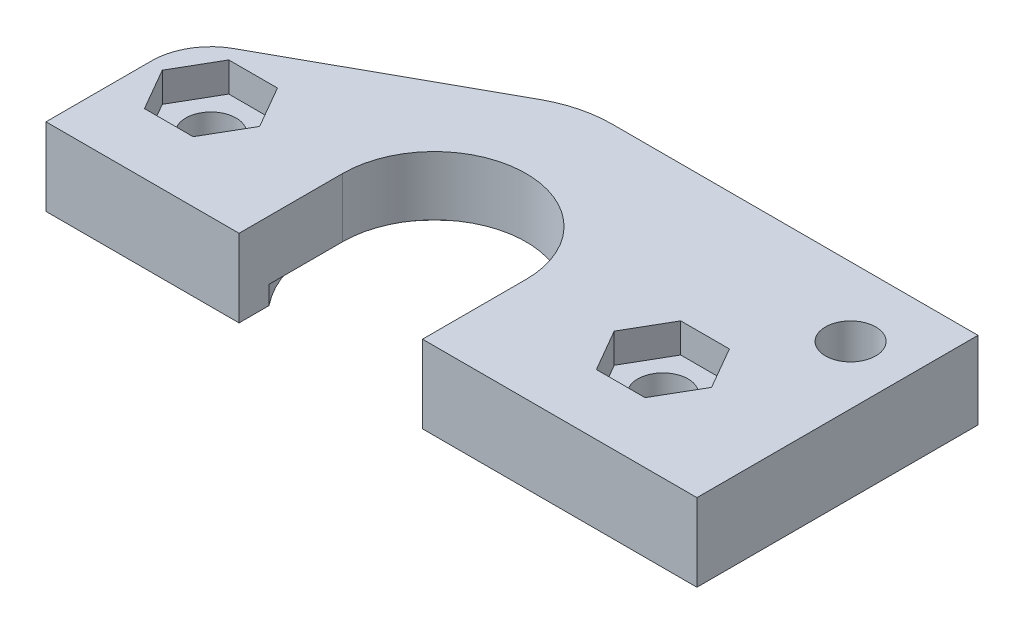
SolidWorks part; units mm, degrees
material "ABS"
ref_plane "Plano frontal" through (0, 0, 0) normal (0, 0, 1) x (1, 0, 0)
ref_plane "Plano superior" through (0, 0, 0) normal (0, 1, 0) x (1, 0, 0)
ref_plane "Plano direito" through (0, 0, 0) normal (1, 0, 0) x (0, 0, -1)
sketch "Esboço1" plane through (0, 0, 0) normal (0, 1, 0) x (1, 0, 0)
  line L0 (13.05, 0) -> (13.05, 7)
  line L1 (0, 0) -> (13.05, 0)
  line L2 (0, 0) -> (0, 9.5)
  line L3 (17.2, 19) -> (44, 19)
  line L4 (44, 0) -> (44, 19)
  line L5 (25.45, 0) -> (25.45, 7)
  line L6 (25.45, 0) -> (44, 0)
  line L7 (0, 9.5) -> (17.2, 19)
  circle A0 centre (4.2, 6.95) radius 1.7
  circle A1 centre (34.75, 6.95) radius 1.7
  circle A2 centre (40.05, 14.3377) radius 1.7
  arc A3 (25.45, 7) -> (13.05, 7) centre (19.25, 7) ccw
  dimension "D3" = 3.4
  dimension "D8" = 3.4
  dimension "D11" = 3.4
  dimension "D13" = 12.4
  dimension "D1" = 44
  dimension "D2" = 19
  dimension "D4" = 4.2
  dimension "D5" = 6.95
  dimension "D6" = 13.05
  dimension "D7" = 12.4
  dimension "D9" = 6.95
  dimension "D10" = 9.25
  dimension "D12" = 3.95
  dimension "D14" = 6.2
  dimension "D15" = 9.5
  dimension "D16" = 26.8
  dimension "D17" = 7
extrude "Ressalto-extrusão1" add sketch "Esboço1" along normal blind 5.25
sketch "Esboço2" plane through (0, 0, 0) normal (0, 1, 0) x (1, 0, 0)
  circle A0 centre (19.25, 7) radius 7.95
extrude "Corte-extrusão1" cut sketch "Esboço2" along normal blind 1.25
fillet "Filete1" radius 4 1 edges at (0, 2.625, -9.5)
fillet "Filete2" radius 8 1 edges at (17.2, 2.625, -19)
sketch "Esboço3" plane through (0, 5.25, 0) normal (0, -1, 0) x (-1, 0, 0)
  line L1 (-31.4591, 6.95) -> (-33.1046, 9.8)
  line L2 (-33.1046, 9.8) -> (-36.3954, 9.8)
  line L3 (-36.3954, 9.8) -> (-38.0409, 6.95)
  line L4 (-38.0409, 6.95) -> (-36.3954, 4.1)
  line L5 (-36.3954, 4.1) -> (-33.1046, 4.1)
  line L6 (-33.1046, 4.1) -> (-31.4591, 6.95)
  line L7 (-0.9091, 6.95) -> (-2.5546, 9.8)
  line L8 (-2.5546, 9.8) -> (-5.8454, 9.8)
  line L9 (-5.8454, 9.8) -> (-7.4909, 6.95)
  line L10 (-7.4909, 6.95) -> (-5.8454, 4.1)
  line L11 (-5.8454, 4.1) -> (-2.5546, 4.1)
  line L12 (-2.5546, 4.1) -> (-0.9091, 6.95)
  circle A0 centre (-34.75, 6.95) radius 2.85 construction
  circle A1 centre (-4.2, 6.95) radius 2.85 construction
  point P10 (-1.7318, 5.525)
  dimension "D1" = 5.7
  dimension "D2" = 5.7
extrude "Corte-extrusão2" cut sketch "Esboço3" along normal blind 2
equation "\"D4@Esboço1\"=2.5+\"D3@Esboço1\"/2"
equation "\"D5@Esboço1\"=5.25+\"D3@Esboço1\"/2"
equation "\"D8@Esboço1\"=\"D3@Esboço1\""
equation "\"D9@Esboço1\"=\"D5@Esboço1\""
equation "\"D10@Esboço1\"=7.55+\"D8@Esboço1\"/2"
equation "\"D11@Esboço1\"=\"D3@Esboço1\""
equation "\"D12@Esboço1\"=2.25+\"D11@Esboço1\"/2"
equation "\"D13@Esboço1\"=\"D7@Esboço1\""
equation "\"D14@Esboço1\"=\"D7@Esboço1\"/2"
